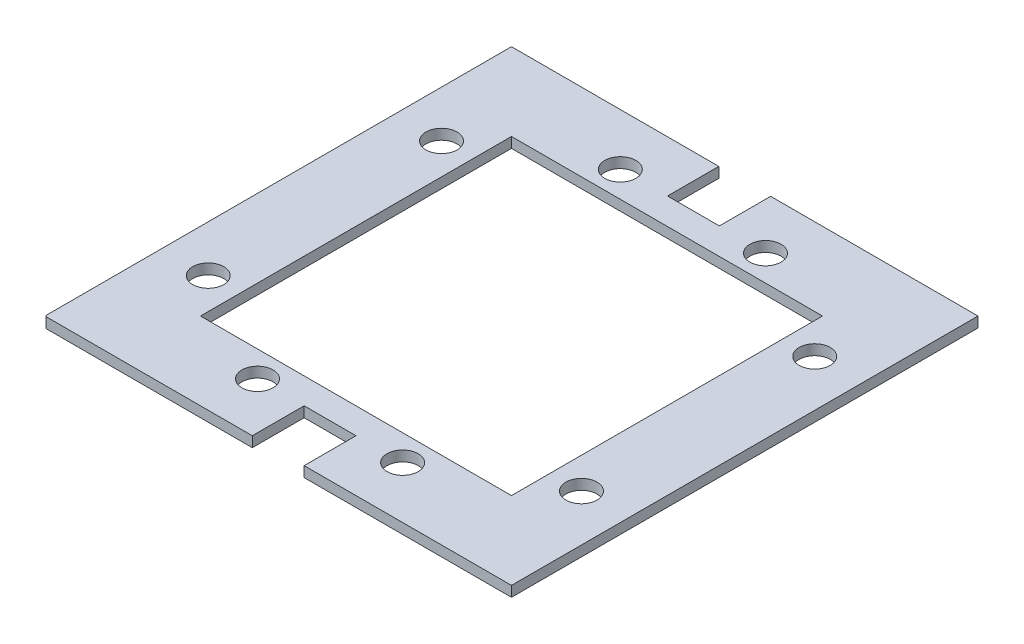
SolidWorks part; units mm, degrees
ref_plane "Alzado" through (0, 0, 0) normal (0, 0, 1) x (1, 0, 0)
ref_plane "Planta" through (0, 0, 0) normal (0, 1, 0) x (1, 0, 0)
ref_plane "Vista lateral" through (0, 0, 0) normal (1, 0, 0) x (0, 0, -1)
sketch "Croquis1" plane through (0, 0, 0) normal (0, 1, 0) x (1, 0, 0)
  line L0 (0, 0) -> (30, 30) construction
  line L1 (0, 0) -> (30, 0)
  line L2 (0, 0) -> (0, 30)
  line L3 (0, 30) -> (30, 30)
  line L4 (30, 0) -> (30, 30)
  line L5 (-7.5, -7.5) -> (37.5, -7.5)
  line L6 (-7.5, -7.5) -> (-7.5, 37.5)
  line L7 (-7.5, 37.5) -> (37.5, 37.5)
  line L8 (37.5, -7.5) -> (37.5, 37.5)
  line L9 (-7.5, 37.5) -> (37.5, -7.5) construction
  line L10 (-9.9749, 39.9749) -> (-7.5, 37.5) construction
  line L11 (33, 15) -> (37.5, 15) construction
  line L12 (15, 15) -> (15, -17.4738) construction
  line L13 (15, 15) -> (0, 15) construction
  line L14 (15, 30) -> (15, 37.5) construction
  line L15 (0, 30) -> (30, 30) construction
  line L16 (0, 30) -> (0, 0) construction
  line L17 (0, 0) -> (30, 0) construction
  line L18 (30, 30) -> (30, 0) construction
  line L19 (0, 30) -> (30, 0) construction
  line L20 (0, 0) -> (30, 30) construction
  line L21 (33, 3.75) -> (33, 15) construction
  line L22 (33, 15) -> (33, 26.25) construction
  line L23 (8, 32.5) -> (15, 32.5) construction
  line L24 (15, 32.5) -> (22, 32.5) construction
  circle A4 centre (-3, 26.25) radius 1.5
  circle A5 centre (-3, 3.75) radius 1.5
  arc A12 (-7.5, -7.3985) -> (-7.3985, -7.5) centre (-4.9749, -4.9749) ccw
  circle A18 centre (8, 32.5) radius 1.5
  circle A20 centre (22, 32.5) radius 1.5
  circle A22 centre (22, -2.5) radius 1.5
  circle A23 centre (33, 26.25) radius 1.5
  circle A24 centre (33, 3.75) radius 1.5
  circle A25 centre (8, -2.5) radius 1.5
  point P9 (15, 15)
  point P10 (15, 15)
  dimension "D3" = 18
  dimension "D4" = 3
  dimension "D9" = 3
  dimension "D1" = 30
  dimension "D2" = 45
  dimension "D5" = 3.5
  dimension "D6" = 7
  dimension "D8" = 30
  dimension "D10" = 11.25
  dimension "D7" = 17.5
extrude "Saliente-Extruir1" add sketch "Croquis1" along normal blind 1
sketch "Croquis3" plane through (0, 1, 0) normal (0, 1, 0) x (1, 0, 0)
  line L0 (-7.5, 37.5) -> (37.5, 37.5) construction
  line L1 (12.5, 37.5) -> (17.5, 37.5)
  line L2 (12.5, 37.5) -> (12.5, 32.5508)
  line L3 (12.5, 32.5508) -> (17.5, 32.5508)
  line L4 (17.5, 37.5) -> (17.5, 32.5508)
  line L5 (-7.3985, -7.5) -> (37.5, -7.5) construction
  line L6 (12.5, -7.5) -> (17.5, -7.5)
  line L7 (12.5, -7.5) -> (12.5, -2.5)
  line L8 (12.5, -2.5) -> (17.5, -2.5)
  line L9 (17.5, -7.5) -> (17.5, -2.5)
  line L10 (-7.5, 15.0508) -> (37.5, 15) construction
  line L11 (-7.5, -7.3985) -> (-7.5, 37.5) construction
  line L12 (37.5, -7.5) -> (37.5, 37.5) construction
  line L13 (15, 32.5508) -> (15, 15.0254) construction
  line L14 (15, 15.0254) -> (15, -2.5) construction
  dimension "D1" = 5
  dimension "D2" = 5
extrude "Cortar-Extruir2" cut sketch "Croquis3" against normal blind 10
